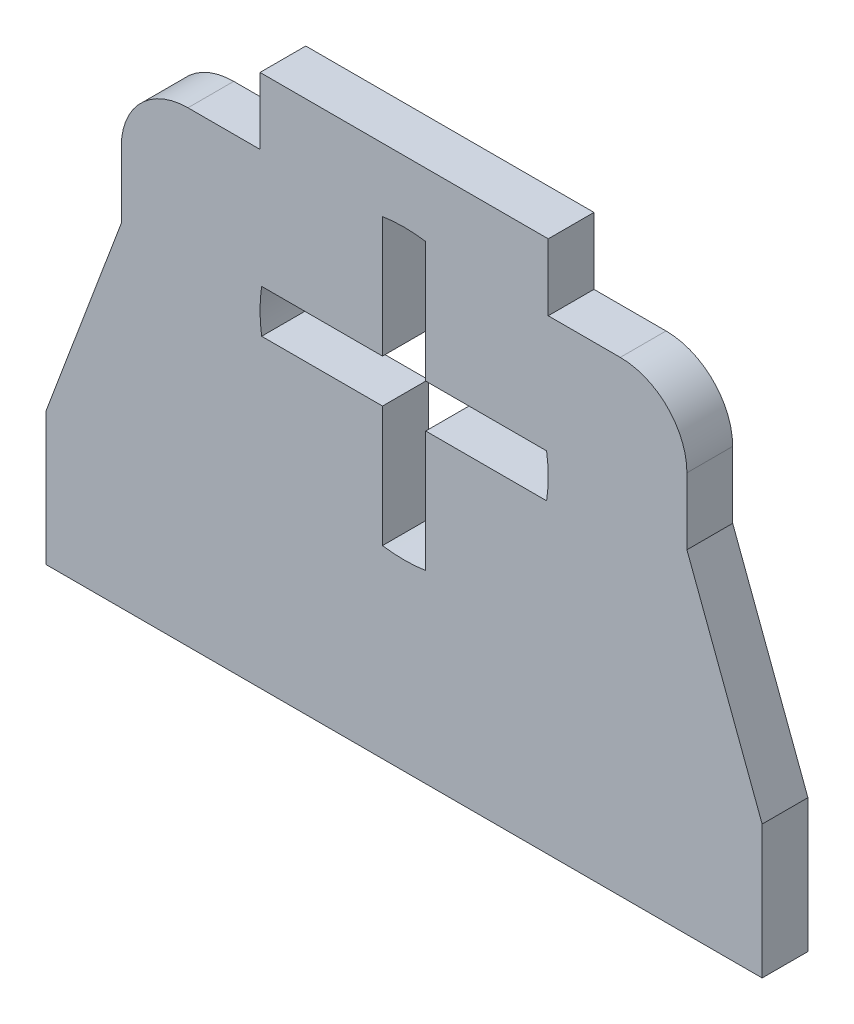
SolidWorks part; units mm, degrees
ref_plane "Front Plane" through (0, 0, 0) normal (0, 0, 1) x (1, 0, 0)
ref_plane "Top Plane" through (0, 0, 0) normal (0, 1, 0) x (1, 0, 0)
ref_plane "Right Plane" through (0, 0, 0) normal (1, 0, 0) x (0, 0, -1)
sketch "Sketch1" plane through (0, 0, 0) normal (0, 1, 0) x (1, 0, 0)
  line L1 (-19.845, 1.5875) -> (19.845, 1.5875)
  line L2 (-19.845, 1.5875) -> (-19.845, -1.5875)
  line L3 (-19.845, -1.5875) -> (19.845, -1.5875)
  line L4 (19.845, 1.5875) -> (19.845, -1.5875)
  line L5 (-19.845, 1.5875) -> (19.845, -1.5875) construction
  line L6 (-19.845, -1.5875) -> (19.845, 1.5875) construction
  point P0 (0, 0)
  dimension "D1" = 3.175
  dimension "D2" = 39.69
extrude "Boss-Extrude1" add sketch "Sketch1" along normal blind 12.7
ref_plane "Plane1" through (0, 0, 1.5875) normal (0, 0, 1) x (1, 0, 0)
sketch "Sketch3" plane through (0, 0, 1.5875) normal (0, 0, 1) x (1, 0, 0)
  line L0 (-9.0656, 9.525) -> (-1.5875, 9.525)
  line L3 (-1.5875, 12.7) -> (1.5875, 12.7)
  line L5 (1.5875, 0) -> (-1.5875, 0)
  line L7 (1.5875, 12.7) -> (1.5875, 9.525)
  line L8 (1.5875, 9.525) -> (9.0656, 9.525)
  line L9 (-1.5875, 9.525) -> (-1.5875, 12.7)
  line L10 (-16.6701, 1.576) -> (-19.845, 1.599)
  line L14 (19.845, 3.175) -> (19.845, 0)
  line L15 (19.845, 0) -> (-16.6701, 1.576)
  line L16 (-19.845, 1.599) -> (-16.6701, 1.576)
  line L17 (-10.6531, 7.9375) -> (-10.6531, 6.35)
  line L18 (19.845, 3.175) -> (19.845, 12.7)
  line L19 (19.845, 12.7) -> (-19.845, 12.7)
  line L20 (-19.845, 12.7) -> (-19.845, 1.599)
  line L21 (-19.845, 1.599) -> (-10.6531, 6.35)
  line L27 (19.845, 0) -> (19.845, 3.175)
  line L28 (19.845, 3.175) -> (10.6531, 6.35)
  line L30 (-16.6701, 1.576) -> (19.845, 0)
  line L31 (10.6531, 7.9375) -> (10.6531, 6.35)
  arc A0 (-10.6531, 7.9375) -> (-9.0656, 9.525) centre (-9.0656, 7.9375) cw
  arc A1 (10.6531, 7.9375) -> (9.0656, 9.525) centre (9.0656, 7.9375) ccw
  point P9 (0, 12.7)
  dimension "D1" = 3.175
  dimension "D3" = 3.175
extrude "Cut-Extrude1" cut sketch "Sketch3" against normal blind 12.7 contours L17 A0 L0 L9 L19 L20 L21 | A1 L31 L28 L18 L19 L7 L8
sketch "Sketch4" plane through (0, 0, 1.5875) normal (0, 0, 1) x (1, 0, 0)
  line L3 (3.175, 6.55) -> (3.175, 6.15)
  line L4 (-3.175, 6.55) -> (-3.175, 6.15)
  line L5 (-3.175, 6.55) -> (3.175, 6.55)
  line L6 (3.175, 6.15) -> (-3.175, 6.15)
  line L7 (-0.2, 9.525) -> (0.2, 9.525)
  line L8 (0.2, 9.525) -> (0.2, 3.175)
  line L9 (0.2, 3.175) -> (0, 3.175)
  line L10 (-0.2, 9.525) -> (-0.2, 3.175)
  line L11 (-0.2, 3.175) -> (0, 3.175)
  point P10 (0, 6.35)
  point P12 (3.175, 6.35)
  point P18 (0, 9.525)
  dimension "D3" = 0.4
  dimension "D4" = 0.4
extrude "Cut-Extrude2" cut sketch "Sketch4" against normal blind 12.7 contours L5 L8 L6 L3 | L10 L5 L4 L6
sketch "Sketch5" plane through (0, 0, 1.5875) normal (0, 0, 1) x (1, 0, 0)
  line L0 (-19.845, 0) -> (19.845, 0)
  line L1 (19.845, 0) -> (19.845, 3.175)
  line L2 (19.845, 3.175) -> (10.6531, 6.35)
  line L3 (10.6531, 6.35) -> (10.6531, 7.9375)
  line L4 (-19.845, 0) -> (-19.845, 1.599)
  line L5 (-19.845, 1.599) -> (-10.6531, 6.35)
  line L6 (-10.6531, 6.35) -> (-10.6531, 7.9375)
  line L7 (-9.0656, 9.525) -> (-1.5875, 9.525)
  line L8 (-1.5875, 9.525) -> (-1.5875, 12.7)
  line L9 (-1.5875, 9.525) -> (-1.5875, 12.7) construction
  line L10 (-1.5875, 12.7) -> (1.5875, 12.7)
  line L11 (1.5875, 12.7) -> (1.5875, 9.525)
  line L12 (1.5875, 9.525) -> (9.0656, 9.525)
  line L17 (19.845, 0) -> (24.845, 0)
  line L18 (-19.845, 0) -> (-24.845, 0)
  line L19 (-24.845, 0) -> (-24.845, 37)
  line L20 (24.845, 0) -> (24.845, 37)
  line L21 (24.845, 37) -> (-24.845, 37)
  line L22 (-15, 37) -> (15, 37)
  arc A0 (-10.6531, 7.9375) -> (-9.0656, 9.525) centre (-9.0656, 7.9375) cw
  arc A1 (9.0656, 9.525) -> (10.6531, 7.9375) centre (9.0656, 7.9375) cw
  arc A2 (10.6531, 7.9375) -> (9.0656, 9.525) centre (9.0656, 7.9375) ccw construction
  point P42 (0, 37)
  dimension "D1" = 5
  dimension "D2" = 5
  dimension "D3" = 37
  dimension "D4" = 30
extrude "Boss-Extrude2" add sketch "Sketch5" against normal blind 3.175 contours L12 A1 L3 L2 L1 L17 L20 L21 L19 L18 L4 L5 L6 A0 L7 L8 L10 L11
sketch "Sketch6" plane through (0, 0, 1.5875) normal (0, 0, 1) x (1, 0, 0)
  line L0 (-24.845, 37) -> (-24.845, 0)
  line L1 (-24.845, 0) -> (24.845, 0)
  line L2 (24.845, 0) -> (24.845, 37)
  line L3 (24.845, 37) -> (10, 37)
  line L4 (-10, 37) -> (10, 37)
  line L5 (10, 37) -> (-10, 37)
  line L6 (-24.845, 37) -> (-24.845, 18.5)
  line L7 (10, 32.375) -> (15, 32.375)
  line L8 (-10, 37) -> (10, 37)
  line L9 (24.845, 37) -> (10, 37)
  line L10 (-10, 37) -> (-24.845, 37)
  line L12 (-24.845, 27.75) -> (-24.845, 18.5)
  line L15 (-19.625, 27.75) -> (-19.625, 23.125)
  line L18 (-10, 37) -> (10, 37)
  line L20 (-15, 32.375) -> (-10, 32.375)
  line L21 (-10, 37) -> (-10, 32.375)
  line L22 (10, 37) -> (10, 32.375)
  line L25 (19.625, 23.125) -> (19.625, 27.75)
  line L26 (-24.845, 18.5) -> (-24.845, 0)
  line L27 (24.845, 18.5) -> (24.845, 0)
  line L28 (-24.845, 9.25) -> (-19.625, 23.125)
  line L29 (19.625, 23.125) -> (24.845, 9.25)
  arc A0 (-15, 32.375) -> (-19.625, 27.75) centre (-15, 27.75) ccw
  arc A1 (15, 32.375) -> (19.625, 27.75) centre (15, 27.75) cw
  point P11 (0, 37)
  point P26 (0, 37)
  line M1 (-24.845, 37) -> (-24.845, 0)
  line M4 (24.845, 37) -> (-24.845, 37)
  dimension "D2" = 20
extrude "Cut-Extrude3" cut sketch "Sketch6" against normal blind 3.175 contours A0 L20 L21 L6 L0 L28 L15 M4 M1 | L7 A1 L25 L29 L27 L2 L22 M4
sketch "Sketch7" plane through (0, 0, 1.5875) normal (0, 0, 1) x (1, 0, 0)
  line L0 (0.2, 6.15) -> (0.2, 3.175)
  line L1 (0.2, 3.175) -> (-0.2, 3.175)
  line L2 (-0.2, 3.175) -> (-0.2, 6.15)
  line L3 (-0.2, 6.15) -> (-3.175, 6.15)
  line L4 (-3.175, 6.15) -> (-3.175, 6.55)
  line L5 (-3.175, 6.55) -> (-0.2, 6.55)
  line L6 (-0.2, 6.55) -> (-0.2, 9.525)
  line L7 (-0.2, 9.525) -> (0.2, 9.525)
  line L8 (0.2, 9.525) -> (0.2, 6.55)
  line L9 (0.2, 6.55) -> (3.175, 6.55)
  line L10 (3.175, 6.55) -> (3.175, 6.15)
  line L11 (3.175, 6.15) -> (0.2, 6.15)
extrude "Boss-Extrude3" add sketch "Sketch7" against normal blind 3.175
sketch "Sketch8" plane through (0, 0, 1.5875) normal (0, 0, 1) x (1, 0, 0)
  line L0 (-24.845, 0) -> (24.845, 0)
  line L1 (0, 0) -> (0, 9.7)
  line L2 (0, 9.7) -> (0, 12.7)
  line L4 (1.5, 32.5869) -> (1.5, 24.2)
  line L5 (-1.5, 32.5869) -> (-1.5, 24.2)
  line L7 (-9.8869, 24.2) -> (-1.5, 24.2)
  line L8 (-9.8869, 21.2) -> (-1.5, 21.2)
  line L9 (-1.5, 21.2) -> (-1.5, 12.8131)
  line L10 (1.5, 21.2) -> (1.5, 12.8131)
  line L11 (1.5, 21.2) -> (9.8869, 21.2)
  line L12 (1.5, 24.2) -> (9.8869, 24.2)
  circle A0 centre (0, 22.7) radius 10
  point P12 (0, 22.7)
  point P15 (1.5, 22.7)
  point P19 (0, 22.7)
  point P22 (0, 24.2)
  dimension "D3" = 20
  dimension "D1" = 9.7
  dimension "D2" = 13
extrude "Cut-Extrude4" cut sketch "Sketch8" against normal blind 3.175 contours L4 A0 L5 L7 L8 L9 L10 L11 L12
